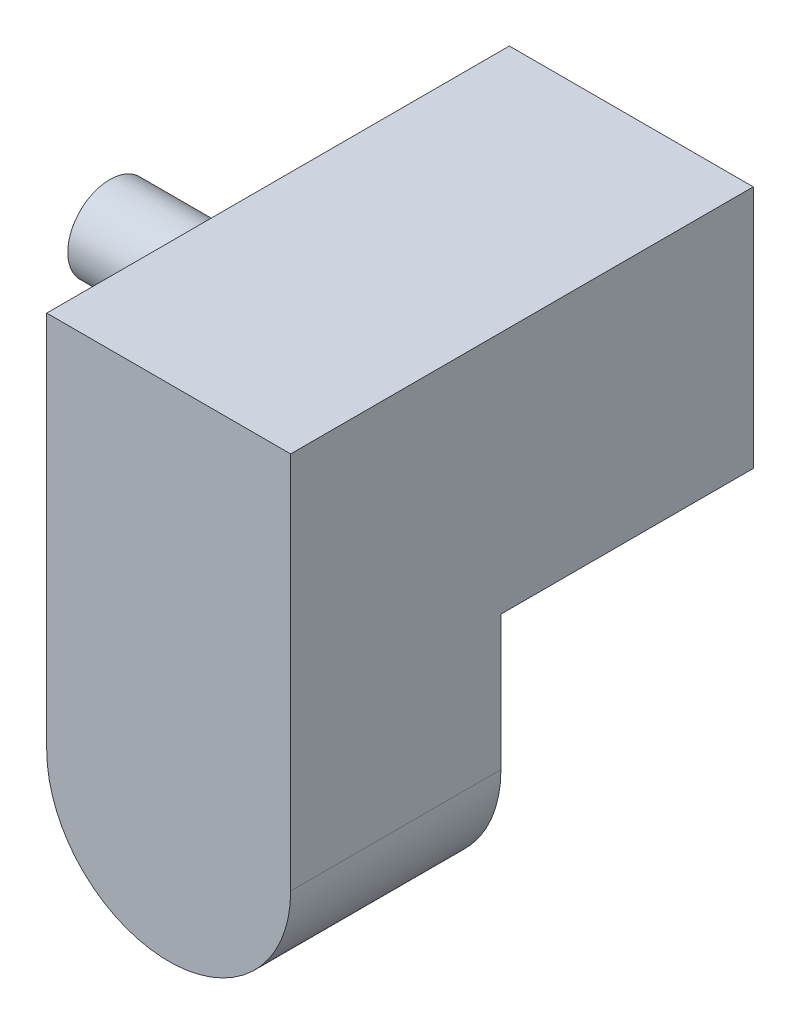
SolidWorks part; units mm, degrees
ref_plane "Front Plane" through (0, 0, 0) normal (0, 0, 1) x (1, 0, 0)
ref_plane "Top Plane" through (0, 0, 0) normal (0, 1, 0) x (1, 0, 0)
ref_plane "Right Plane" through (0, 0, 0) normal (1, 0, 0) x (0, 0, -1)
sketch "Sketch1" plane through (0, 0, 0) normal (0, 0, 1) x (1, 0, 0)
  circle A0 centre (0, 0) radius 36.83
  dimension "D1" = 73.66
extrude "Boss-Extrude1" add sketch "Sketch1" along normal blind 63.5
sketch "Sketch4" plane through (0, 0, 0) normal (0, 0, 1) x (1, 0, 0)
  line L0 (-36.83, 0) -> (36.83, 0)
  line L1 (-36.83, 0) -> (-36.83, 114.3)
  line L2 (36.83, 0) -> (36.83, 114.3)
  line L3 (-36.83, 114.3) -> (36.83, 114.3)
  line L4 (34.925, 0) -> (-34.925, 0) construction
  circle A0 centre (0, 0) radius 36.83 construction
extrude "Boss-Extrude2" add sketch "Sketch4" along normal through all
sketch "Sketch5" plane through (0, 0, 0) normal (0, 0, 1) x (1, 0, 0)
  line L0 (36.83, 0) -> (36.83, 114.3) construction
  line L1 (-36.83, 114.3) -> (36.83, 114.3)
  line L2 (-36.83, 114.3) -> (-36.83, 40.64)
  line L3 (-36.83, 40.64) -> (36.83, 40.64)
  line L4 (36.83, 114.3) -> (36.83, 40.64)
extrude "Boss-Extrude3" add sketch "Sketch5" against normal blind 76.2
sketch "Sketch6" plane through (-36.83, 0, 0) normal (-1, 0, 0) x (0, 0, 1)
  line L1 (63.5, 114.3) -> (-76.2, 114.3) construction
  line L2 (-76.2, 114.3) -> (-76.2, 40.64) construction
  line L3 (63.5, 114.3) -> (63.5, 0) construction
  circle A0 centre (-6.35, 76.2) radius 12.7
  point P10 (0, 0)
  dimension "D1" = 25.4
  dimension "D2" = 38.1
  dimension "D3" = 139.7
  dimension "D4" = 69.85
extrude "Boss-Extrude4" add sketch "Sketch6" along normal blind 50.8
sketch "Sketch2" plane through (0, 0, 0) normal (0, 0, 1) x (1, 0, 0)
  circle A0 centre (0, 0) radius 13.97
  dimension "D1" = 27.94
extrude "Cut-Extrude1" cut sketch "Sketch2" along normal blind 48.26
